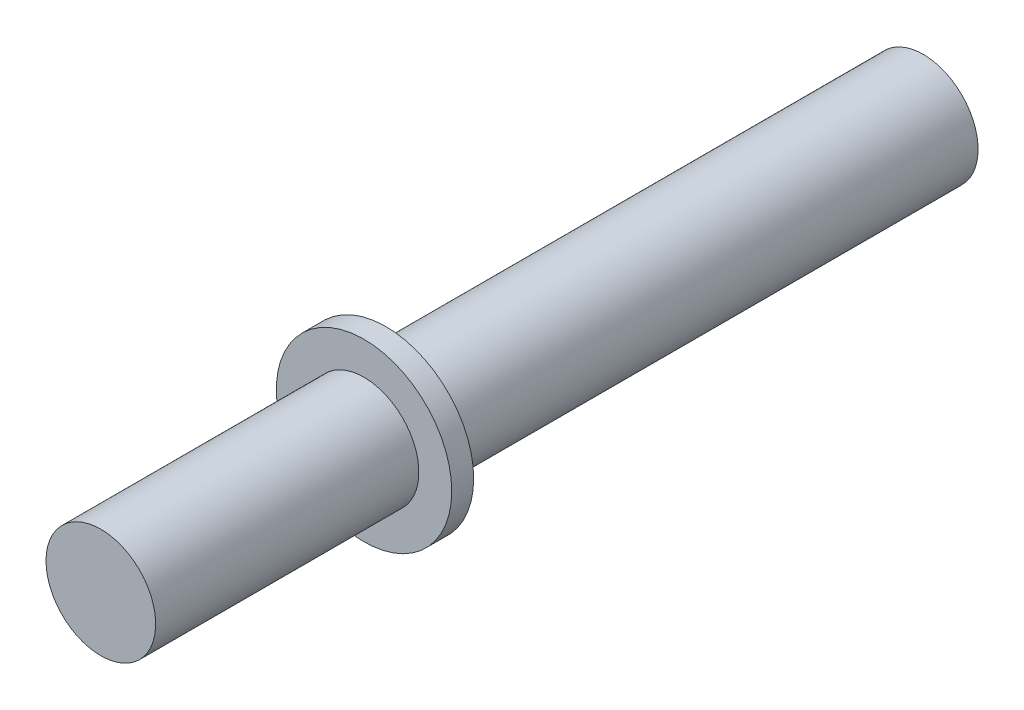
SolidWorks part; units mm, degrees
material "PVC Rigid"
ref_plane "Front Plane" through (0, 0, 0) normal (0, 0, 1) x (1, 0, 0)
ref_plane "Top Plane" through (0, 0, 0) normal (0, 1, 0) x (1, 0, 0)
ref_plane "Right Plane" through (0, 0, 0) normal (1, 0, 0) x (0, 0, -1)
sketch "Sketch1" plane through (0, 0, 0) normal (0, 0, 1) x (1, 0, 0)
  circle A0 centre (-32.0187, -34.6434) radius 1.5
extrude "Plunger_stem" add sketch "Sketch1" along normal blind 22.5 from offset 21.5
sketch "Sketch2" plane through (0, 0, 0) normal (0, 0, 1) x (1, 0, 0)
  circle A0 centre (-32.0187, -34.6434) radius 2.4
extrude "Captive_shoulder" add sketch "Sketch2" along normal blind 0.6 from offset 36.2
